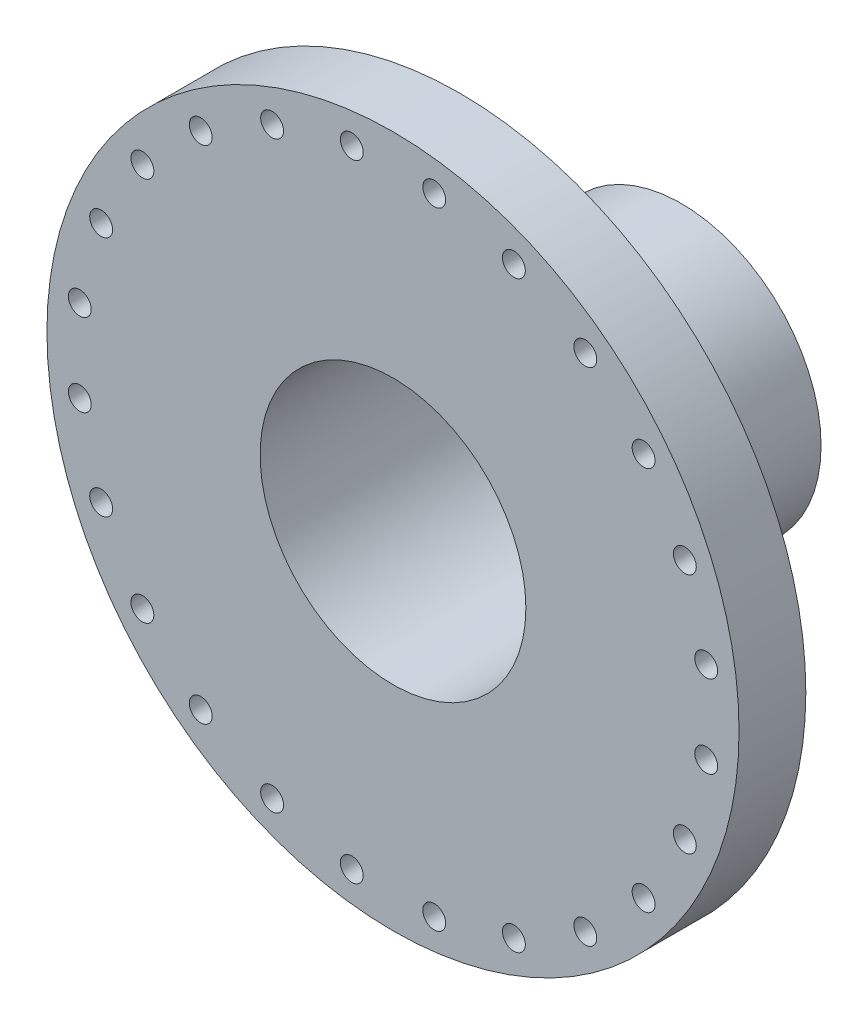
SolidWorks part; units mm, degrees
ref_plane "Front Plane" through (0, 0, 0) normal (0, 0, 1) x (1, 0, 0)
ref_plane "Top Plane" through (0, 0, 0) normal (0, 1, 0) x (1, 0, 0)
ref_plane "Right Plane" through (0, 0, 0) normal (1, 0, 0) x (0, 0, -1)
sketch "Sketch1" plane through (0, 0, 0) normal (0, 0, 1) x (1, 0, 0)
  circle A0 centre (0, 0) radius 51.308
  circle A1 centre (0, 0) radius 48.768
  dimension "D1" = 2.54
  dimension "D2" = 97.536
extrude "Extrude1" add sketch "Sketch1" against normal blind 81.28
sketch "Sketch2" plane through (0, 0, 0) normal (0, 0, 1) x (1, 0, 0)
  circle A0 centre (0, 0) radius 48.768
  circle A1 centre (0, 0) radius 127
  circle A2 centre (0, 0) radius 48.768 construction
extrude "Extrude2" add sketch "Sketch2" along normal blind 24.511
sketch "Sketch3" plane through (0, 0, 24.511) normal (0, 0, 1) x (1, 0, 0)
  circle A0 centre (15.1313, -114.9338) radius 4.2
extrude "Cut-Extrude1" cut sketch "Sketch3" against normal up to next
pattern_circular "CirPattern1" count 24 over 360 about axis through (0, 0, 0) along (0, 0, 1) of "Cut-Extrude1"
sketch "Sketch4" plane through (0, 0, -81.28) normal (0, 0, -1) x (-1, 0, 0)
  circle A0 centre (0, 0) radius 51.308
  circle A1 centre (0, 0) radius 25.4
  circle A2 centre (0, 0) radius 51.308 construction
  dimension "D1" = 50.8
extrude "Extrude3" add sketch "Sketch4" against normal blind 2.54
